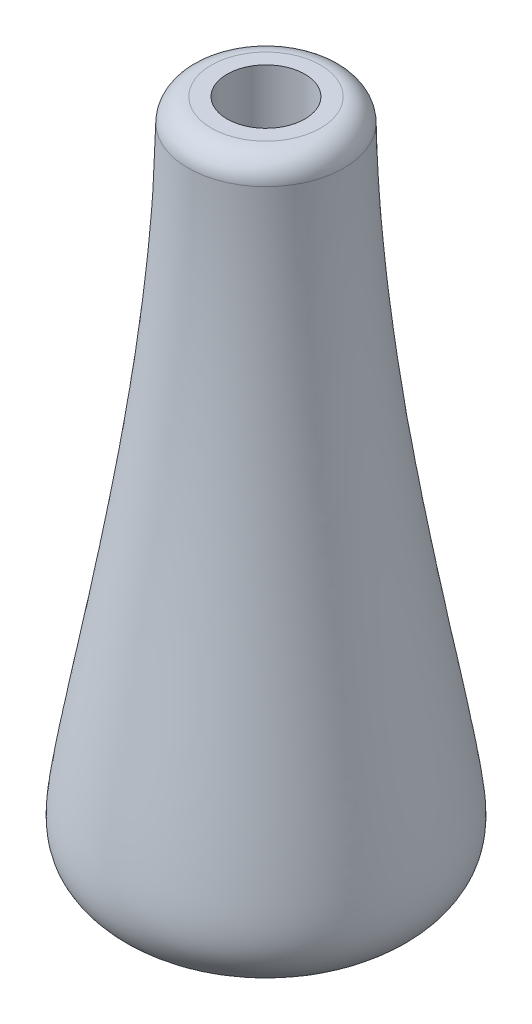
SolidWorks part; units mm, degrees
ref_plane "Front Plane" through (0, 0, 0) normal (0, 0, 1) x (1, 0, 0)
ref_plane "Top Plane" through (0, 0, 0) normal (0, 1, 0) x (1, 0, 0)
ref_plane "Right Plane" through (0, 0, 0) normal (1, 0, 0) x (0, 0, -1)
sketch "Sketch1" plane through (0, 0, 0) normal (1, 0, 0) x (0, 0, -1)
  line L0 (0, 0) -> (0, 90)
  line L1 (0, 90) -> (10, 90)
  line L3 (-7.8619, 0) -> (8.1381, 0) construction
  line L4 (10, 63.6066) -> (10, 116.94) construction
  line L5 (20, 6.1354) -> (20, 18.7437) construction
  spline S0 degree 3 poles (10, 90) (10, 60) (18.8198, 22.8052) (20.9288, 2.4149) (9, 0) (0, 0) knots 0 0 0 0 0.550031 0.650031 1 1 1 1
  point P7 (0, 45)
  dimension "D4" = 100
  dimension "D5" = 30
  dimension "D6" = 60
  dimension "D1" = 10
  dimension "90" = 90
  dimension "D2" = 10
  dimension "D3" = 20
revolve "Revolve1" add sketch "Sketch1" angle 360 about L0
sketch "Sketch2" plane through (0, 90, 0) normal (0, 1, 0) x (1, 0, 0)
  circle A0 centre (0, 0) radius 5
  dimension "D1" = 10
extrude "Cut-Extrude2" cut sketch "Sketch2" against normal blind 70 contours A0
fillet "Fillet1" radius 3 1 edges at (0, 90, -10)
